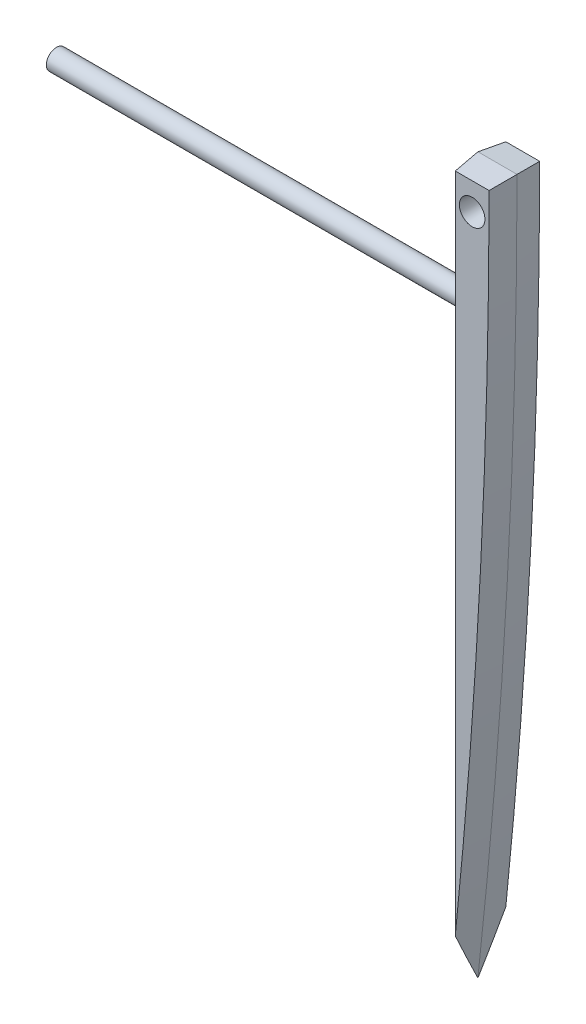
SolidWorks part; units mm, degrees
ref_plane "Front Plane" through (0, 0, 0) normal (0, 0, 1) x (1, 0, 0)
ref_plane "Top Plane" through (0, 0, 0) normal (0, 1, 0) x (1, 0, 0)
ref_plane "Right Plane" through (0, 0, 0) normal (1, 0, 0) x (0, 0, -1)
sketch "Sketch1" plane through (0, 0, 0) normal (0, 0, 1) x (1, 0, 0)
  line L1 (0, 37.1209) -> (3.8668, 37.1209)
  line L2 (0, 37.1209) -> (0, -33.5856)
  arc A0 (3.8668, 37.1209) -> (0, -33.5856) centre (-644.5265, 37.1209) cw
  circle A1 centre (1.9334, 34.1861) radius 1
extrude "Boss-Extrude1" add sketch "Sketch1" along normal mid plane 5 draft 6
sketch "Sketch2" plane through (0, 0, 0) normal (1, 0, 0) x (0, 0, -1)
  line L0 (0, 37.1209) -> (0, -33.5856) construction
  circle A0 centre (0, 24.2308) radius 1
sketch "Sketch3" plane through (0, 0, 0) normal (0, 0, 1) x (1, 0, 0)
  line L1 (0, 37.1209) -> (0, -33.5856) construction
  line L2 (0, 28.7604) -> (-41.6484, 28.7604)
sweep "Sweep1" add profiles "Sketch2" path "Sketch3"
